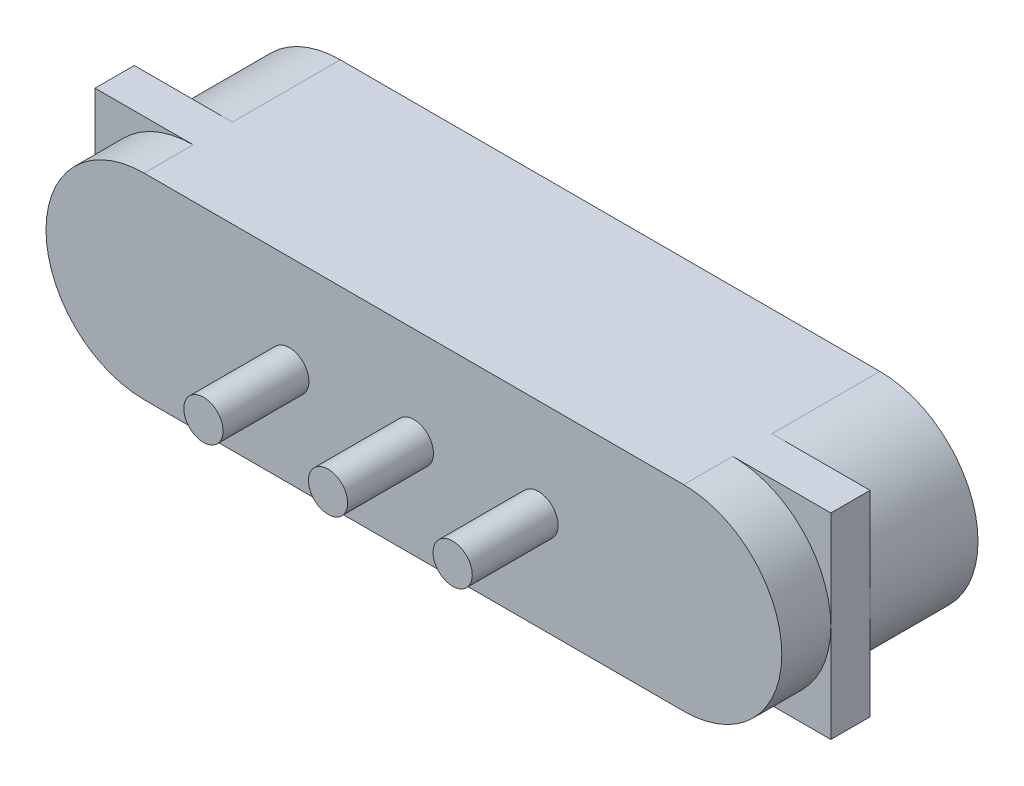
SolidWorks part; units mm, degrees
ref_plane "前视基准面" through (0, 0, 0) normal (0, 0, 1) x (1, 0, 0)
ref_plane "上视基准面" through (0, 0, 0) normal (0, 1, 0) x (1, 0, 0)
ref_plane "右视基准面" through (0, 0, 0) normal (1, 0, 0) x (0, 0, -1)
sketch "草图1" plane through (0, 0, 0) normal (0, 0, 1) x (1, 0, 0)
  line L0 (0, 0) -> (11, 0) construction
  line L1 (0, 2) -> (11, 2)
  line L2 (0, -2) -> (11, -2)
  arc A0 (0, 2) -> (0, -2) centre (0, 0) ccw
  arc A1 (11, -2) -> (11, 2) centre (11, 0) ccw
  point P3 (5.5, 0)
  point P8 (-2, 0)
  point P9 (13, 0)
  dimension "D1" = 15
  dimension "D2" = 4
extrude "凸台-拉伸1" add sketch "草图1" along normal blind 4
sketch "草图2" plane through (0, 0, 0) normal (0, 0, -1) x (-1, 0, 0)
  line L0 (-11, 2) -> (0, 2) construction
  line L1 (-13, 2) -> (2, 2)
  line L2 (-13, 2) -> (-13, -2)
  line L3 (-13, -2) -> (2, -2)
  line L4 (2, 2) -> (2, -2)
  line L5 (0, -2) -> (-11, -2) construction
  arc A0 (-11, 2) -> (-11, -2) centre (-11, 0) ccw construction
  arc A1 (0, -2) -> (0, 2) centre (0, 0) ccw construction
extrude "凸台-拉伸2" add sketch "草图2" against normal blind 0.8 from offset 2.2 offset against normal yes
sketch "草图3" plane through (0, 0, 0) normal (0, 0, -1) x (-1, 0, 0)
  line L0 (-11, 2) -> (0, 2) construction
  circle A0 centre (-8.04, 0) radius 0.5
  circle A1 centre (-5.5, 0) radius 0.5
  circle A2 centre (-2.96, 0) radius 0.5
  point P8 (-5.5, 2)
  point P9 (-5.5, 0.1883)
  dimension "D1" = 1
  dimension "D2" = 1
  dimension "D3" = 1
  dimension "D4" = 2.54
  dimension "D5" = 2.54
extrude "凸台-拉伸3" add sketch "草图3" along normal blind 1
fillet "圆角1" radius 0.5 3 edges at (7.54, 0, -1) (5, 0, -1) (2.46, 0, -1)
sketch "草图4" plane through (0, 0, 4) normal (0, 0, 1) x (1, 0, 0)
  circle A95 centre (2.96, 0) radius 0.4
  circle A96 centre (2.96, 0) radius 0.4
  circle A99 centre (5.5, 0) radius 0.4
  circle A100 centre (5.5, 0) radius 0.4
  circle A102 centre (8.04, 0) radius 0.4
  circle A103 centre (8.04, 0) radius 0.4
  dimension "D2" = 0.1
  dimension "D1" = 0.1
  dimension "D3" = 0.1
extrude "凸台-拉伸4" add sketch "草图4" along normal blind 1.75
sketch "草图7" plane through (0, 0, 0) normal (0, 0, -1) x (-1, 0, 0)
  line L2 (0, 2) -> (-11, 2)
  line L3 (-11, -2) -> (0, -2)
  line L4 (0, 2) -> (-11, 2)
  line L5 (-11, -2) -> (0, -2)
  arc A2 (0, -2) -> (0, 2) centre (0, 0) ccw
  arc A3 (-11, 2) -> (-11, -2) centre (-11, 0) ccw
  arc A4 (0, -2) -> (0, 2) centre (0, 0) ccw
  arc A5 (-11, 2) -> (-11, -2) centre (-11, 0) ccw
  dimension "D1" = 0
extrude "切除-拉伸1" cut sketch "草图7" along normal blind 1.75
sketch "草图8" plane through (0, 0, 0) normal (0, 0, -1) x (-1, 0, 0)
  circle A2 centre (-8.04, 0) radius 0.5
  circle A3 centre (-8.04, 0) radius 0.5
  circle A10 centre (-5.5, 0) radius 0.5
  circle A11 centre (-5.5, 0) radius 0.5
  circle A13 centre (-2.96, 0) radius 0.5
  circle A14 centre (-2.96, 0) radius 0.5
  dimension "D1" = 0.1
  dimension "D2" = 0.1
  dimension "D3" = 0.1
extrude "切除-拉伸2" cut sketch "草图8" against normal blind 0.1
